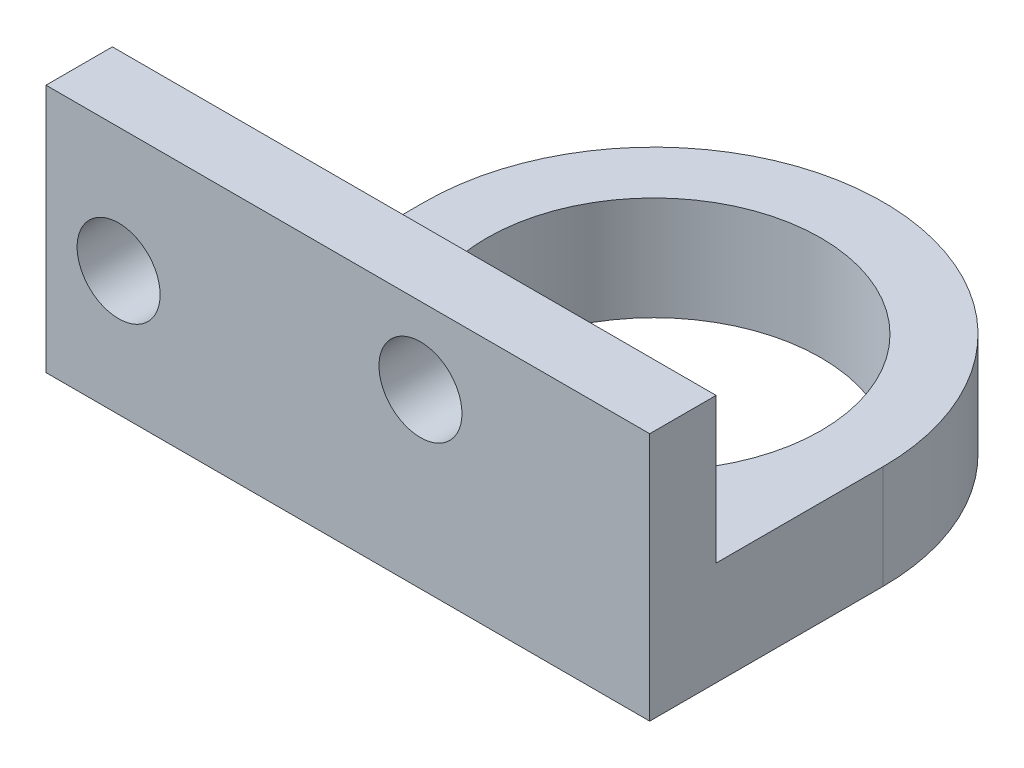
SolidWorks part; units mm, degrees
ref_plane "Front Plane" through (0, 0, 0) normal (0, 0, 1) x (1, 0, 0)
ref_plane "Top Plane" through (0, 0, 0) normal (0, 1, 0) x (1, 0, 0)
ref_plane "Right Plane" through (0, 0, 0) normal (1, 0, 0) x (0, 0, -1)
sketch "Sketch1" plane through (0, 0, 0) normal (0, 1, 0) x (1, 0, 0)
  line L0 (11.05, 0) -> (11.05, -11.05)
  line L1 (11.05, -11.05) -> (0, -11.05)
  line L2 (-11.05, 0) -> (-11.05, -11.05)
  line L3 (-11.05, -11.05) -> (0, -11.05)
  circle A0 centre (0, 0) radius 8.05
  arc A1 (11.05, 0) -> (-11.05, 0) centre (0, 0) ccw
  circle A3 centre (0, 0) radius 11.05 construction
  point P10 (11.1, 0)
  dimension "D1" = 3
extrude "Boss-Extrude1" add sketch "Sketch1" along normal blind 5
sketch "Sketch2" plane through (0, 0, 11.05) normal (0, 0, 1) x (1, 0, 0)
  line L0 (0, 5) -> (0, 12)
  line L1 (11.05, 0) -> (-18.05, 0)
  line L2 (11.05, 0) -> (11.05, 12)
  line L3 (11.05, 12) -> (-18.05, 12)
  line L4 (-18.05, 0) -> (-18.05, 12)
  line L5 (-11.05, 5) -> (11.05, 5) construction
  line L6 (-11.05, 5) -> (-11.05, 0) construction
  line L7 (-11.05, 5) -> (-11.05, 12)
  line L8 (-18.05, 6) -> (-11.05, 6)
  circle A0 centre (0, 8.3139) radius 2
  circle A1 centre (-14.55, 6) radius 2
  line M6 (11.05, 5) -> (-11.05, 5)
  line M7 (-11.05, 5) -> (-11.05, 0)
  dimension "D1" = 7
extrude "Boss-Extrude2" add sketch "Sketch2" against normal blind 3 contours A1 L8 L4 L1 L7 M7 | A1 L8 L7 L3 L4 | A0 L0 L3 L7 M6 | A0 L0 L2 L3 M6
sketch "Sketch4" plane through (0, 0, 11.05) normal (0, 0, 1) x (1, 0, 0)
  line L4 (11.05, 0) -> (11.05, 12)
  line L5 (11.05, 12) -> (-18.05, 12)
  line L6 (-18.05, 12) -> (-18.05, 0)
  line L7 (-18.05, 0) -> (11.05, 0)
  line L8 (11.05, 0) -> (11.05, 12)
  line L9 (11.05, 12) -> (-18.05, 12)
  line L10 (-18.05, 12) -> (-18.05, 0)
  line L11 (-18.05, 0) -> (11.05, 0)
  circle A1 centre (0, 8.3139) radius 2
  circle A2 centre (0, 8.3139) radius 2
  circle A3 centre (-14.55, 6) radius 2
  circle A4 centre (-14.55, 6) radius 2
  dimension "D1" = 0
  dimension "D2" = 0
  dimension "D3" = 0
extrude "Boss-Extrude3" add sketch "Sketch4" along normal blind 0.2
